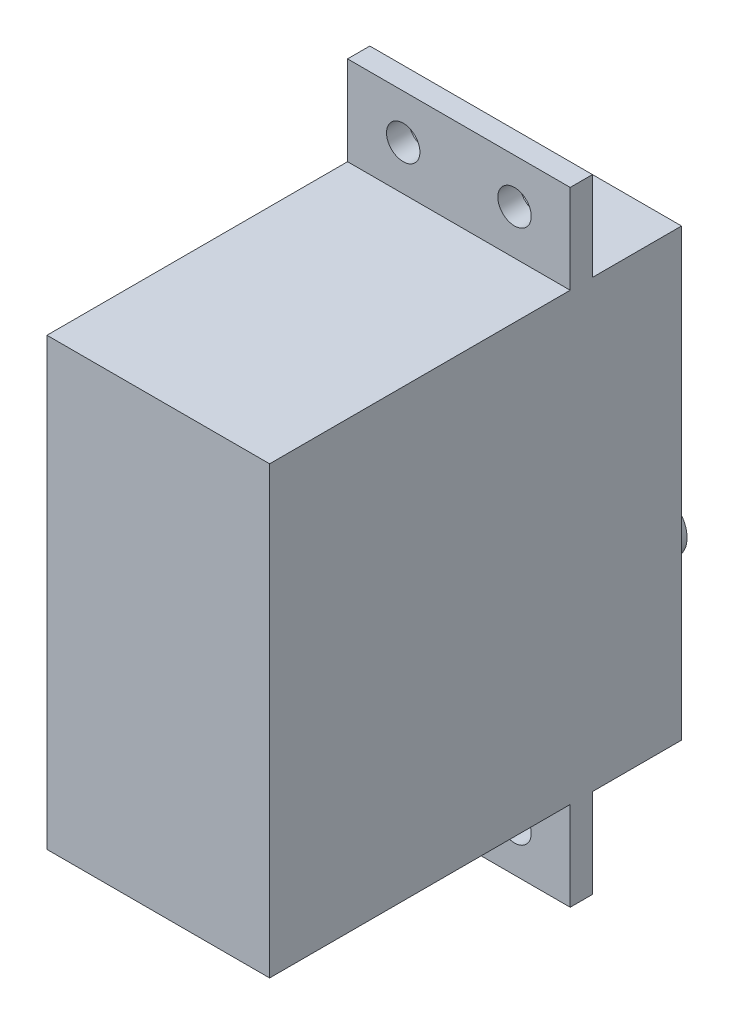
SolidWorks part; units mm, degrees
ref_plane "Front Plane" through (0, 0, 0) normal (0, 0, 1) x (1, 0, 0)
ref_plane "Top Plane" through (0, 0, 0) normal (0, 1, 0) x (1, 0, 0)
ref_plane "Right Plane" through (0, 0, 0) normal (1, 0, 0) x (0, 0, -1)
sketch "Sketch1" plane through (0, 0, 0) normal (0, 0, 1) x (1, 0, 0)
  line L1 (-10, -20) -> (10, -20)
  line L2 (-10, -20) -> (-10, 20)
  line L3 (-10, 20) -> (10, 20)
  line L4 (10, -20) -> (10, 20)
  line L5 (-10, -20) -> (10, 20) construction
  line L6 (-10, 20) -> (10, -20) construction
  point P0 (0, 0)
  dimension "D1" = 40
  dimension "D2" = 20
extrude "Boss-Extrude1" add sketch "Sketch1" along normal blind 37
sketch "Sketch2" plane through (0, 20, 0) normal (0, 1, 0) x (1, 0, 0)
  line L0 (-10, -37) -> (-10, 0) construction
  line L1 (-10, -10) -> (10, -10)
  line L2 (-10, -10) -> (-10, -8)
  line L3 (-10, -8) -> (10, -8)
  line L4 (10, -10) -> (10, -8)
  line L5 (10, -37) -> (10, 0) construction
  line L7 (10, 0) -> (-10, 0) construction
  dimension "D1" = 8
  dimension "D2" = 2
extrude "Boss-Extrude2" add sketch "Sketch2" along normal blind 8
sketch "Sketch3" plane through (0, 0, 0) normal (0, 0, 1) x (1, 0, 0)
  line L0 (0, 36.5046) -> (0, 0) construction
  line L2 (-10, 28) -> (10, 28) construction
  circle A0 centre (5, 24) radius 1.5
  circle A2 centre (-5, 24) radius 1.5
  dimension "D2" = 3
  dimension "D1" = 4
  dimension "D3" = 5
extrude "Cut-Extrude2" cut sketch "Sketch3" against normal through all and the other way through all
mirror "Mirror3" about plane through (0, 0, 0) normal (0, 1, 0) of "Cut-Extrude2", "Boss-Extrude2"
sketch "Sketch4" plane through (0, 0, 0) normal (0, 0, -1) x (-1, 0, 0)
  line L3 (10, -20) -> (-10, -20) construction
  circle A0 centre (0, -12) radius 2.5
  point P2 (0, 0)
  point P8 (0, 0)
  dimension "D2" = 5
  dimension "D1" = 8
extrude "Boss-Extrude3" add sketch "Sketch4" along normal blind 8
